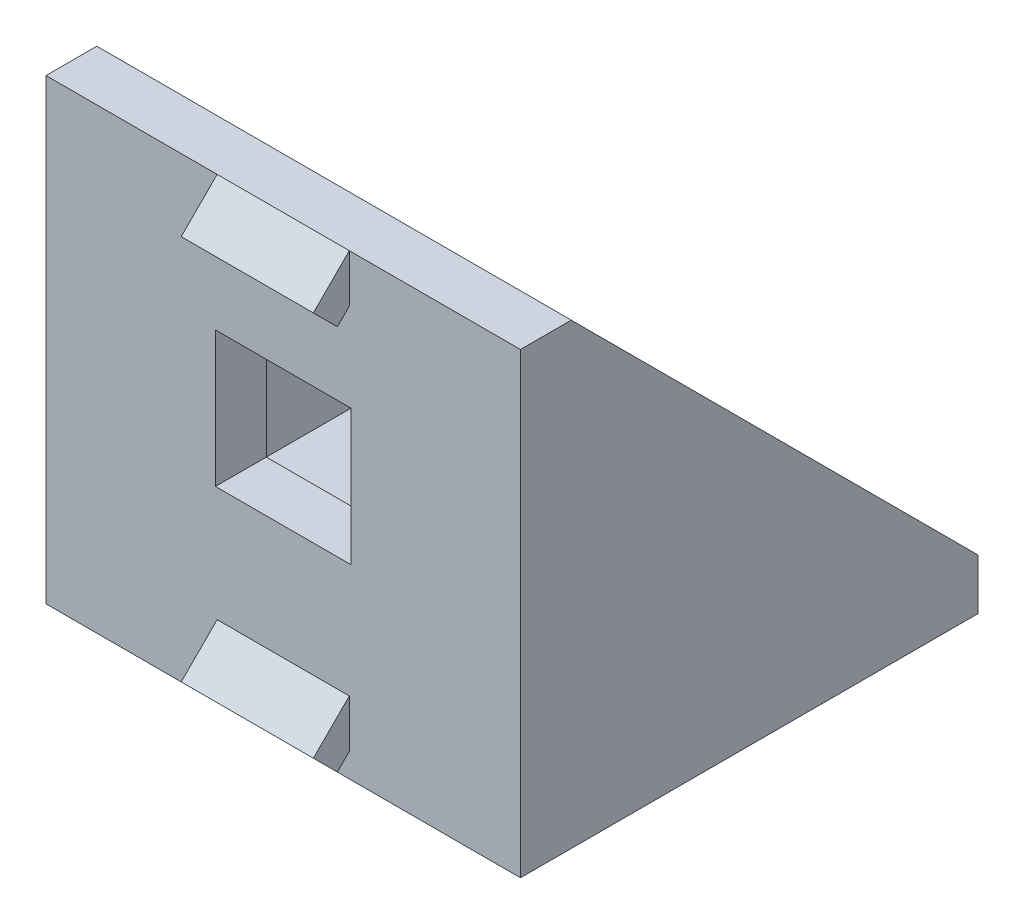
SolidWorks part; units mm, degrees
ref_plane "Front Plane" through (0, 0, 0) normal (0, 0, 1) x (1, 0, 0)
ref_plane "Top Plane" through (0, 0, 0) normal (0, 1, 0) x (1, 0, 0)
ref_plane "Right Plane" through (0, 0, 0) normal (1, 0, 0) x (0, 0, -1)
sketch "Sketch1" plane through (0, 0, 0) normal (1, 0, 0) x (0, 0, -1)
  line L0 (0, 0) -> (0, 27)
  line L1 (0, 0) -> (27, 0)
  line L2 (0, 27) -> (3, 27)
  line L3 (3, 27) -> (27, 3)
  line L4 (27, 3) -> (27, 0)
  dimension "D1" = 27
  dimension "D2" = 27
  dimension "D3" = 3
  dimension "D4" = 3
extrude "Boss-Extrude1" add sketch "Sketch1" along normal blind 28
sketch "Sketch2" plane through (0, 0, -27) normal (0, 0, -1) x (-1, 0, 0)
  line L0 (-28, 3) -> (0, 3) construction
  line L1 (-2, 3) -> (-26, 3)
  line L2 (-2, 3) -> (-2, 27)
  line L3 (-2, 27) -> (-26, 27)
  line L4 (-26, 3) -> (-26, 27)
  line L5 (-28, 27) -> (0, 27) construction
  line L6 (-28, 3) -> (-28, 27) construction
  line L7 (0, 3) -> (0, 27) construction
  dimension "D1" = 2
  dimension "D2" = 2
extrude "Cut-Extrude1" cut sketch "Sketch2" against normal offset from surface (24 mm away) 3 up to face at (14, 13.5, 0)
sketch "Sketch3" plane through (0, 0, -3) normal (0, 0, -1) x (-1, 0, 0)
  line L0 (-26, 27) -> (-2, 27) construction
  line L1 (-10, 19) -> (-18, 19)
  line L2 (-10, 19) -> (-10, 11)
  line L3 (-10, 11) -> (-18, 11)
  line L4 (-18, 19) -> (-18, 11)
  line L5 (-2, 3) -> (-26, 3) construction
  line L6 (-2, 27) -> (-2, 3) construction
  line L7 (-26, 3) -> (-26, 27) construction
  dimension "D1" = 8
  dimension "D2" = 8
  dimension "D3" = 8
  dimension "D4" = 8
extrude "Cut-Extrude2" cut sketch "Sketch3" against normal up to next
sketch "Sketch4" plane through (0, 3, 0) normal (0, 1, 0) x (1, 0, 0)
  line L0 (2, 3) -> (26, 3) construction
  line L1 (10, 11) -> (18, 11)
  line L2 (10, 11) -> (10, 19)
  line L3 (10, 19) -> (18, 19)
  line L4 (18, 11) -> (18, 19)
  line L5 (26, 27) -> (2, 27) construction
  line L6 (2, 3) -> (2, 27) construction
  line L7 (26, 3) -> (26, 27) construction
  dimension "D1" = 8
  dimension "D2" = 8
  dimension "8" = 8
  dimension "D3" = 8
extrude "Cut-Extrude3" cut sketch "Sketch4" against normal up to next
ref_plane "Plane1" through (14, 0, 0) normal (1, 0, 0) x (0, 0, -1)
sketch "Sketch5" plane through (14, 0, 0) normal (1, 0, 0) x (0, 0, -1)
  line L0 (27, 0) -> (24.8787, -2.1213)
  line L1 (24.8787, -2.1213) -> (23.4645, -0.7071)
  line L2 (23.4645, -0.7071) -> (24.1716, 0)
  line L3 (0, 0) -> (27, 0) construction
  line L4 (2.1213, -2.1213) -> (0.7071, -0.7071)
  line L5 (4.2426, 0) -> (2.1213, -2.1213)
  line L6 (0.7071, -0.7071) -> (1.4142, 0)
  line L7 (0, 27) -> (0, 0) construction
  line L8 (0, 1.4142) -> (-0.7071, 0.7071)
  line L9 (-0.7071, 0.7071) -> (-2.1213, 2.1213)
  line L10 (-2.1213, 2.1213) -> (0, 4.2426)
  line L11 (-0.7071, 23.4645) -> (-2.1213, 24.8787)
  line L12 (-2.1213, 24.8787) -> (0, 27)
  line L13 (0, 24.1716) -> (-0.7071, 23.4645)
  line L14 (24.1716, 0) -> (27, 0)
  line L15 (1.4142, 0) -> (4.2426, 0)
  line L16 (0, 1.4142) -> (0, 4.2426)
  line L17 (0, 27) -> (0, 24.1716)
  dimension "D1" = 3
  dimension "D2" = 2
  dimension "D3" = 45
  dimension "D4" = 1
  dimension "D5" = 3
  dimension "D6" = 45
  dimension "D7" = 2
  dimension "D8" = 3
  dimension "D9" = 1
  dimension "D10" = 45
  dimension "D11" = 3
  dimension "D12" = 1
  dimension "D13" = 2
  dimension "D14" = 45
extrude "Boss-Extrude2" add sketch "Sketch5" along normal mid plane 7.8
sketch "Sketch7" plane through (14, 0, 0) normal (1, 0, 0) x (0, 0, -1)
  line L0 (3, 19) -> (3, 11) construction
  line L1 (11, 3) -> (19, 3) construction
  point P0 (3, 15)
  point P1 (15, 3)
